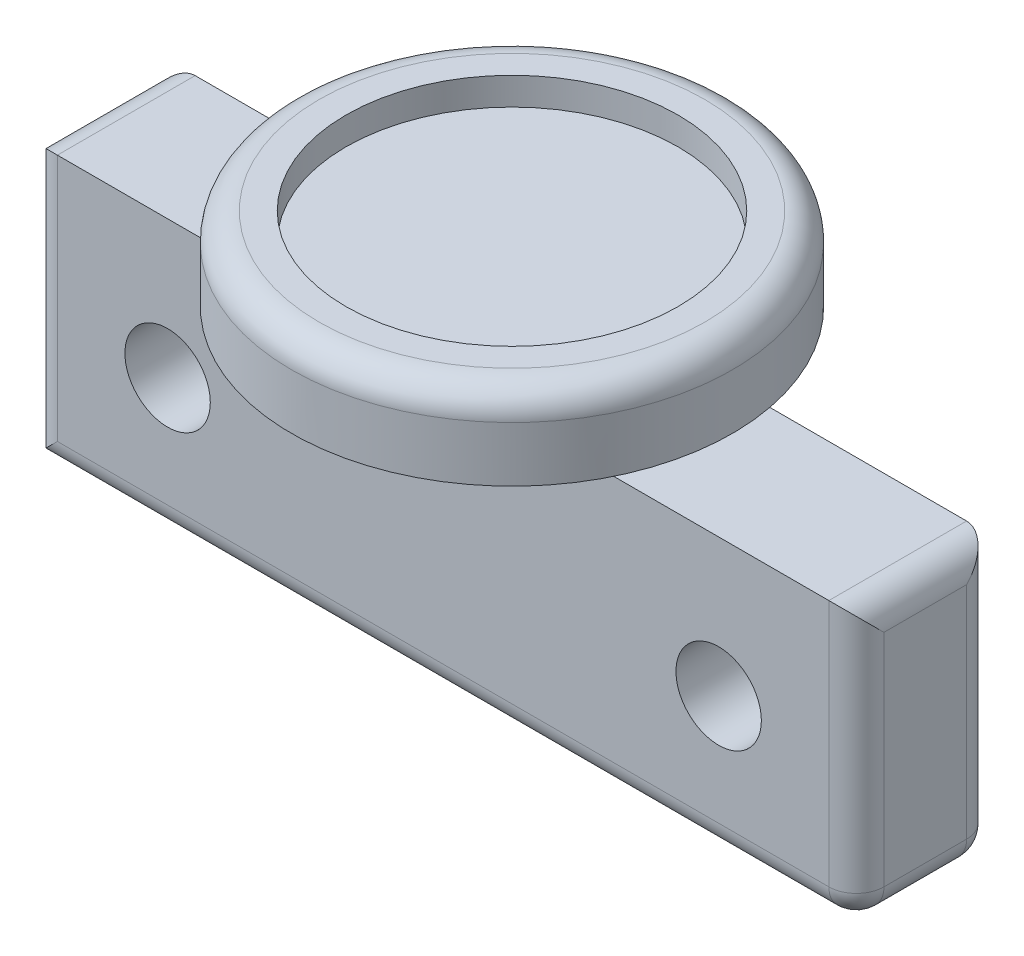
SolidWorks part; units mm, degrees
material "PET"
ref_plane "Front Plane" through (0, 0, 0) normal (0, 0, 1) x (1, 0, 0)
ref_plane "Top Plane" through (0, 0, 0) normal (0, 1, 0) x (1, 0, 0)
ref_plane "Right Plane" through (0, 0, 0) normal (1, 0, 0) x (0, 0, -1)
sketch "Sketch1" plane through (0, 0, 0) normal (0, 0, 1) x (1, 0, 0)
  line L1 (-38.1, 12.7) -> (38.1, 12.7)
  line L2 (-38.1, 12.7) -> (-38.1, -12.7)
  line L3 (-38.1, -12.7) -> (38.1, -12.7)
  line L4 (38.1, 12.7) -> (38.1, -12.7)
  line L5 (-38.1, 12.7) -> (38.1, -12.7) construction
  line L6 (-38.1, -12.7) -> (38.1, 12.7) construction
  point P0 (0, 0)
  dimension "D1" = 76.2
  dimension "D2" = 25.4
extrude "Boss-Extrude1" add sketch "Sketch1" along normal mid plane 12.7
sketch "Sketch5" plane through (0, 12.7, 0) normal (0, 1, 0) x (1, 0, 0)
  circle A0 centre (0, 0) radius 12.7
  dimension "D1" = 25.4
extrude "Boss-Extrude3" add sketch "Sketch5" along normal blind 2.54
sketch "Sketch7" plane through (0, 15.24, 0) normal (0, 1, 0) x (1, 0, 0)
  circle A0 centre (0, 0) radius 20.32
  dimension "D1" = 40.64
extrude "Boss-Extrude4" add sketch "Sketch7" along normal blind 7.62
sketch "Sketch8" plane through (0, 22.86, 0) normal (0, 1, 0) x (1, 0, 0)
  circle A0 centre (0, 0) radius 15.3051
extrude "Cut-Extrude1" cut sketch "Sketch8" against normal blind 2.54
fillet "Fillet3" radius 2.54 1 edges at (0, 22.86, 20.32)
fillet "Fillet4" radius 2.54 9 edges at (38.1, -12.7, 0) (0, -12.7, -6.35) (38.1, 0, -6.35) (38.1, 12.7, 0) (-38.1, 12.7, 0) (-38.1, 0, -6.35) (-38.1, 0, 6.35) (38.1, 0, 6.35) (0, -12.7, 6.35)
hole_wizard "#97 (0.31) Diameter Hole1" positions "Sketch11" profile "Sketch10" hole size "#97" standard "ANSI Inch"
sketch "Sketch11" plane through (0, 0, 6.35) normal (0, 0, 1) x (1, 0, 0)
  line L0 (-35.56, 12.7) -> (-35.56, -10.16) construction
  point P0 (25.4, 0)
  point P2 (-25.4, 0)
  dimension "D1" = 10.16
  dimension "D2" = 50.8
sketch "Sketch10" plane through (25.4, 0, 6.35) normal (1, 0, 0) x (0, -1, 0)
  line L0 (0, 0) -> (0, 27.7656)
  line L1 (0, 27.7656) -> (3.937, 25.4)
  line L2 (3.937, 25.4) -> (3.937, 0)
  line L5 (3.937, 0) -> (0, 0)
  line L10 (0, 27.7656) -> (-3.937, 25.4) construction
  line L11 (0, -6.35) -> (0, 107.95) construction
  dimension "Hole Dia." = 7.874
  dimension "Hole Depth" = 25.4
  dimension "Drill Angle" = 118
